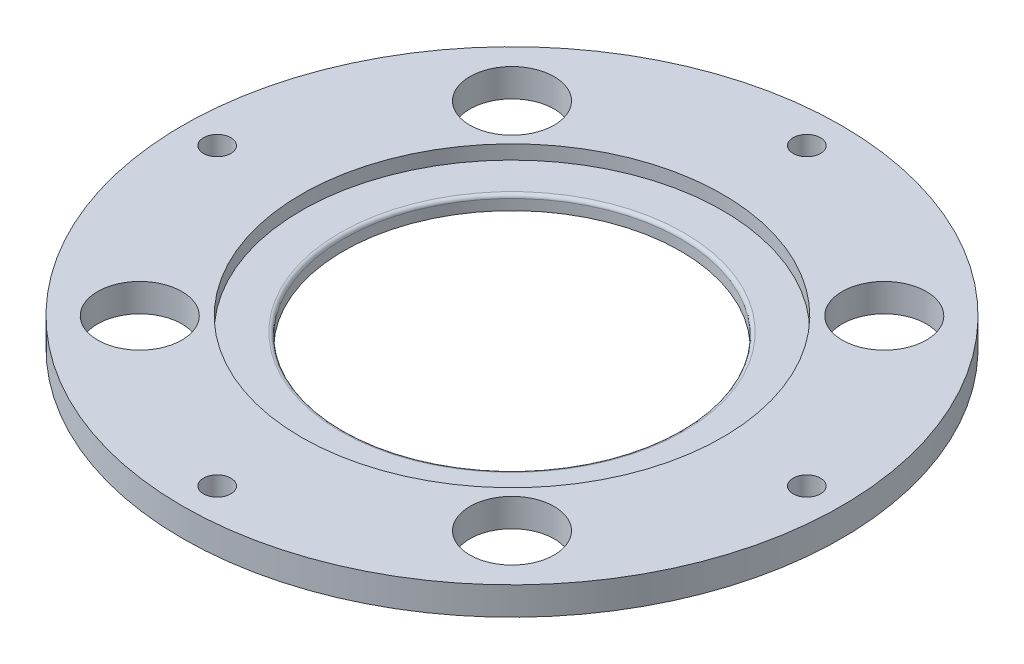
SolidWorks part; units mm, degrees
ref_plane "Front Plane" through (0, 0, 0) normal (0, 0, 1) x (1, 0, 0)
ref_plane "Top Plane" through (0, 0, 0) normal (0, 1, 0) x (1, 0, 0)
ref_plane "Right Plane" through (0, 0, 0) normal (1, 0, 0) x (0, 0, -1)
sketch "Sketch1" plane through (0, 0, 0) normal (0, 1, 0) x (1, 0, 0)
  line L0 (0, 0) -> (0, 42) construction
  circle A0 centre (0, 42) radius 1.95
  circle A2 centre (0, 0) radius 42 construction
  circle A3 centre (0, 0) radius 42 construction
  circle A4 centre (42, 0) radius 1.95
  circle A5 centre (0, 0) radius 42 construction
  circle A6 centre (0, -42) radius 1.95
  circle A7 centre (0, 0) radius 42 construction
  circle A8 centre (-42, 0) radius 1.95
  circle A10 centre (0, 42) radius 4.95 construction
  circle A11 centre (0, 0) radius 42 construction
  circle A12 centre (42, 0) radius 4.95 construction
  circle A13 centre (0, 0) radius 42 construction
  circle A14 centre (0, -42) radius 4.95 construction
  circle A15 centre (0, 0) radius 42 construction
  circle A16 centre (-42, 0) radius 4.95 construction
  circle A17 centre (0, 0) radius 46.95
  circle A18 centre (0, 0) radius 30
  point P18 (0, 0)
  point P29 (0, 0)
  dimension "D1" = 3.9
  dimension "D4" = 3
  dimension "D6" = 60
  dimension "D2" = 42
  dimension "D3" = 4
  dimension "D5" = 4
extrude "Boss-Extrude1" add sketch "Sketch1" along normal mid plane 4
sketch "Sketch2" plane through (0, -2, 0) normal (0, -1, 0) x (1, 0, 0)
  circle A0 centre (0, 0) radius 24
  circle A1 centre (0, 0) radius 30 construction
  circle A2 centre (0, 0) radius 30
  dimension "D1" = 6
extrude "Boss-Extrude2" add sketch "Sketch2" along direction (0, 1, 0) on the side against the normal up to surface (2 mm away) up to plane "Top Plane"
sketch "Sketch3" plane through (0, 2, 0) normal (0, 1, 0) x (1, 0, 0)
  line L0 (0, 0) -> (-26.5165, 26.5165) construction
  line L1 (0, 0) -> (-11.7149, 0) construction
  circle A0 centre (-42, 0) radius 1.95 construction
  circle A1 centre (-42, 0) radius 1.95
  circle A3 centre (0, 0) radius 37.5 construction
  circle A4 centre (-26.5165, 26.5165) radius 6
  circle A5 centre (26.5165, 26.5165) radius 6
  circle A6 centre (26.5165, -26.5165) radius 6
  circle A7 centre (-26.5165, -26.5165) radius 6
  point P9 (0, 0)
  point P10 (0, 0)
  point P18 (0, 0)
  dimension "D2" = 75
  dimension "D3" = 12
  dimension "D1" = 45
  dimension "D4" = 4
extrude "Cut-Extrude1" cut sketch "Sketch3" against normal blind 33
fillet "Fillet1" radius 0.5 1 edges at (0, 0, 24)
